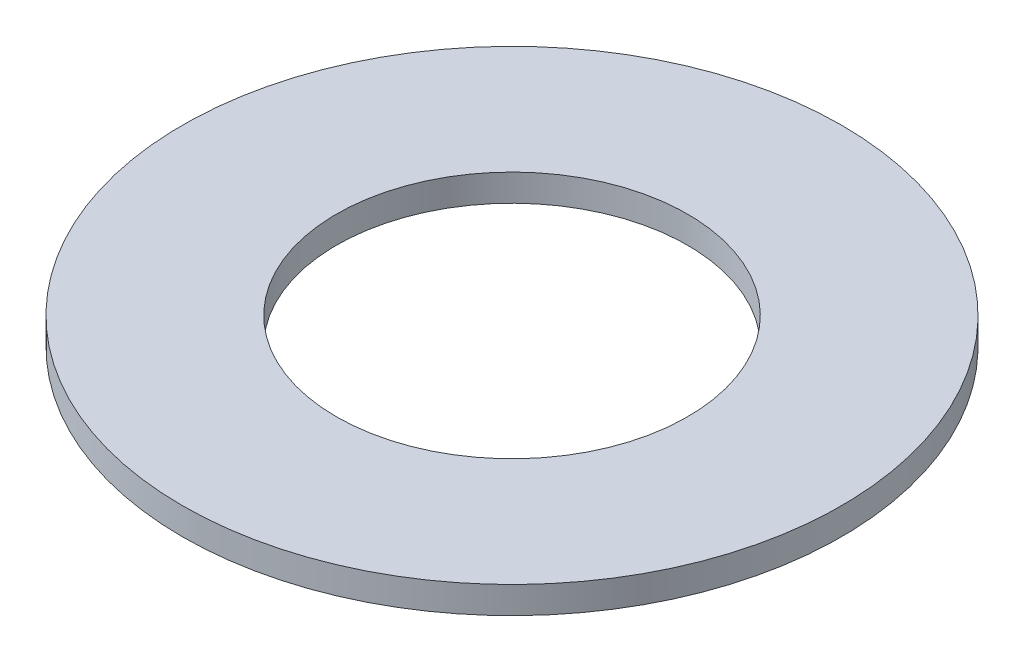
SolidWorks part; units mm, degrees
ref_plane "Front Plane" through (0, 0, 0) normal (0, 0, 1) x (1, 0, 0)
ref_plane "Top Plane" through (0, 0, 0) normal (0, 1, 0) x (1, 0, 0)
ref_plane "Right Plane" through (0, 0, 0) normal (1, 0, 0) x (0, 0, -1)
sketch "Sketch1" plane through (0, 0, 0) normal (0, 1, 0) x (1, 0, 0)
  circle A0 centre (0, 0) radius 7.9375
  circle A1 centre (0, 0) radius 4.229
  dimension "D1" = 15.875
  dimension "D2" = 8.458
extrude "Boss-Extrude1" add sketch "Sketch1" along normal blind 0.65 contours A1
